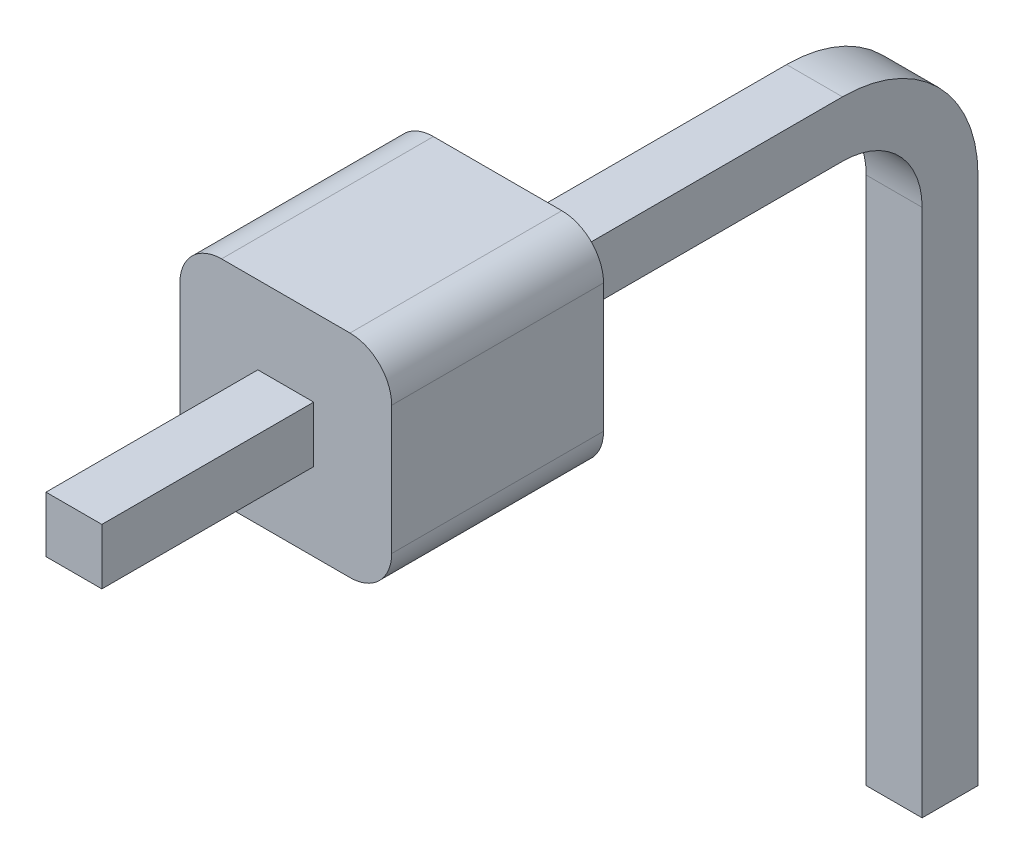
SolidWorks part; units mm, degrees
ref_plane "前视基准面" through (0, 0, 0) normal (0, 0, 1) x (1, 0, 0)
ref_plane "上视基准面" through (0, 0, 0) normal (0, 1, 0) x (1, 0, 0)
ref_plane "右视基准面" through (0, 0, 0) normal (1, 0, 0) x (0, 0, -1)
sketch "草图1" plane through (0, 0, 0) normal (0, 0, 1) x (1, 0, 0)
  line L0 (0, 5.3599) -> (0, -8.0108) construction
  line L1 (-1.27, -0.0191) -> (1.27, -0.0191)
  line L2 (-1.27, -0.0191) -> (-1.27, -2.5591)
  line L3 (-1.27, -2.5591) -> (1.27, -2.5591)
  line L4 (1.27, -0.0191) -> (1.27, -2.5591)
  dimension "D1" = 2.54
  dimension "D2" = 2.54
extrude "拉伸1" add sketch "草图1" along normal blind 2.54
ref_plane "基准面1" through (0, 0, 5.08) normal (0, 0, -1) x (-1, 0, 0)
sketch "草图2" plane through (0, 0, 5.08) normal (0, 0, -1) x (-1, 0, 0)
  line L0 (-1.27, -1.2891) -> (1.27, -1.2891) construction
  line L1 (-1.27, -2.5591) -> (-1.27, -0.0191) construction
  line L2 (1.27, -0.0191) -> (1.27, -2.5591) construction
  line L3 (0, 1.9407) -> (0, -4.2425) construction
  line L5 (-0.335, -0.9541) -> (0.335, -0.9541)
  line L6 (-0.335, -0.9541) -> (-0.335, -1.6241)
  line L7 (-0.335, -1.6241) -> (0.335, -1.6241)
  line L8 (0.335, -0.9541) -> (0.335, -1.6241)
  dimension "D1" = 0.67
  dimension "D2" = 0.67
sketch "草图3" plane through (0, 0, 0) normal (1, 0, 0) x (0, 0, -1)
  line L0 (3.8, -1.2991) -> (-5.08, -1.2991)
  line L3 (5.08, -2.5791) -> (5.08, -8.9191)
  line L8 (-2.54, -0.0191) -> (0, -0.0191) construction
  line L9 (0, -2.5591) -> (0, -0.0191) construction
  arc A0 (5.08, -2.5791) -> (3.8, -1.2991) centre (3.8, -2.5791) ccw
  point P11 (5.08, -1.2991)
  dimension "D5" = 1.28
  dimension "D1" = 5.08
  dimension "D2" = 5.08
  dimension "D3" = 7.62
  dimension "D4" = 1.28
sweep "扫描1" add profiles "草图2" path "草图3"
fillet "圆角1" radius 0.5 4 edges at (1.27, -0.0191, 1.27) (1.27, -2.5591, 1.27) (-1.27, -2.5591, 1.27) (-1.27, -0.0191, 1.27)
equation "\"2.54x2\"=2.54"
